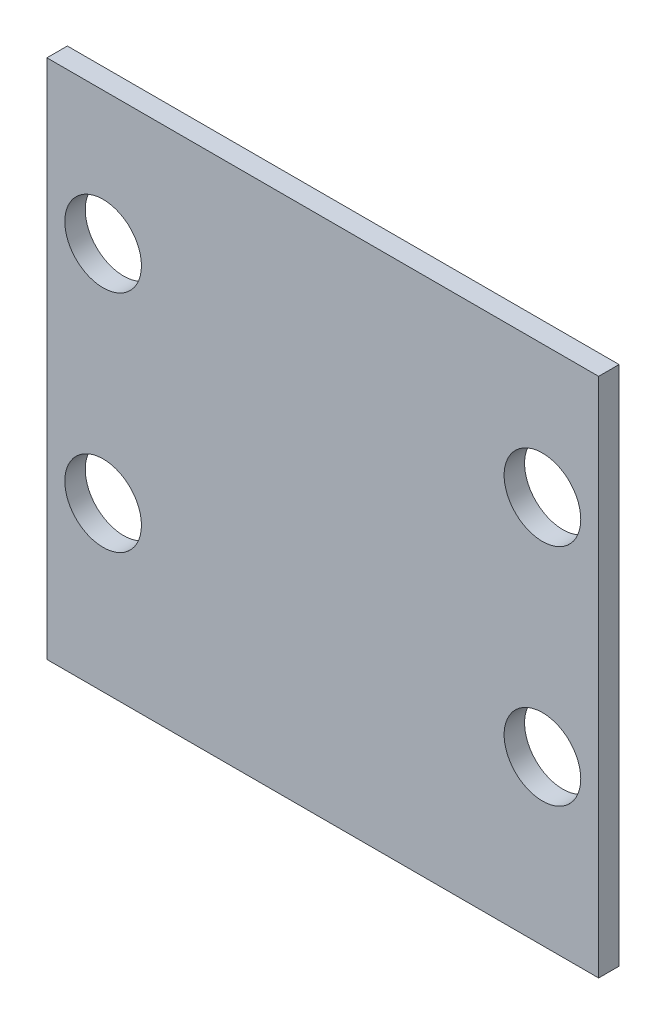
SolidWorks part; units mm, degrees
ref_plane "Alzado" through (0, 0, 0) normal (0, 0, 1) x (1, 0, 0)
ref_plane "Planta" through (0, 0, 0) normal (0, 1, 0) x (1, 0, 0)
ref_plane "Vista lateral" through (0, 0, 0) normal (1, 0, 0) x (0, 0, -1)
sketch "Croquis1" plane through (0, 0, 0) normal (0, 0, 1) x (1, 0, 0)
  line L1 (-27, 25.5) -> (27, 25.5)
  line L2 (-27, 25.5) -> (-27, -25.5)
  line L3 (-27, -25.5) -> (27, -25.5)
  line L4 (27, 25.5) -> (27, -25.5)
  line L5 (-27, 25.5) -> (27, -25.5) construction
  line L6 (-27, -25.5) -> (27, 25.5) construction
  circle A0 centre (-21.5, 12.5) radius 3.75
  circle A1 centre (21.5, 12.5) radius 3.75
  circle A2 centre (21.5, -9.5) radius 3.75
  circle A3 centre (-21.5, -9.5) radius 3.75
  point P0 (0, 0)
  dimension "D3" = 21.5
  dimension "D6" = 21.5
  dimension "D7" = 22
  dimension "D8" = 13
  dimension "D9" = 22
  dimension "D10" = 13
  dimension "D11" = 7.5
  dimension "D12" = 7.5
  dimension "D13" = 7.5
  dimension "D14" = 7.5
  dimension "D1" = 54
  dimension "D2" = 51
  dimension "D4" = 21.5
  dimension "D5" = 21.5
extrude "Saliente-Extruir1" add sketch "Croquis1" against normal blind 2
